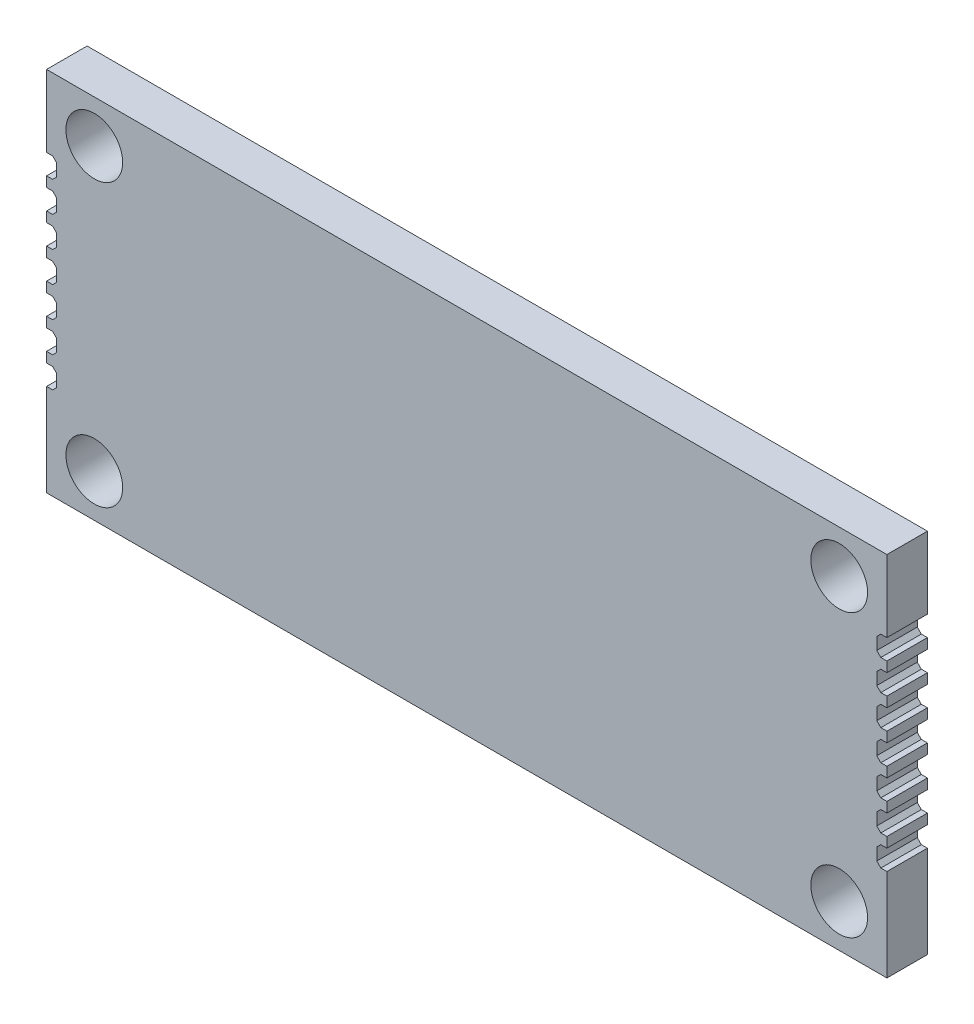
SolidWorks part; units mm, degrees
ref_plane "前视基准面" through (0, 0, 0) normal (0, 0, 1) x (1, 0, 0)
ref_plane "上视基准面" through (0, 0, 0) normal (0, 1, 0) x (1, 0, 0)
ref_plane "右视基准面" through (0, 0, 0) normal (1, 0, 0) x (0, 0, -1)
sketch "草图1" plane through (0, 0, 0) normal (0, 0, 1) x (1, 0, 0)
  line L0 (-20.7373, 13.6) -> (20.7373, 13.6)
  line L1 (20.7373, 13.6) -> (20.7373, -4.5)
  line L2 (20.7373, -4.5) -> (-20.7373, -4.5)
  line L3 (-20.7373, -4.5) -> (-20.7373, 13.6)
extrude "凸台-拉伸1" add sketch "草图1" along normal blind 2
sketch "草图2" plane through (0, 0, 2) normal (0, 0, 1) x (1, 0, 0)
  circle A0 centre (-18.3831, -2.4) radius 1.4
  circle A1 centre (18.3831, -2.4) radius 1.4
  circle A2 centre (18.3831, 11.5) radius 1.4
  circle A3 centre (-18.3831, 11.5) radius 1.4
extrude "切除-拉伸1" cut sketch "草图2" against normal up to next
sketch "草图3" plane through (0, 0, 0) normal (0, 0, -1) x (-1, 0, 0)
  line L0 (-20.7373, 1.05) -> (-20.4373, 1.05) construction
  line L1 (-20.2373, 0.85) -> (-20.4373, 1.05) construction
  line L2 (-20.2373, 0.85) -> (-20.2373, 0.25) construction
  line L3 (-20.4373, 0.05) -> (-20.2373, 0.25) construction
  line L4 (-20.7373, 0.05) -> (-20.4373, 0.05) construction
  line L5 (-20.7373, 1.05) -> (-20.4373, 1.05)
  line L6 (-20.2373, 0.85) -> (-20.4373, 1.05)
  line L7 (-20.2373, 0.85) -> (-20.2373, 0.25)
  line L8 (-20.4373, 0.05) -> (-20.2373, 0.25)
  line L9 (-20.7373, 0.05) -> (-20.4373, 0.05)
  line L10 (-20.7373, 2.55) -> (-20.4373, 2.55)
  line L11 (-20.2373, 2.35) -> (-20.4373, 2.55)
  line L12 (-20.2373, 2.35) -> (-20.2373, 1.75)
  line L13 (-20.4373, 1.55) -> (-20.2373, 1.75)
  line L14 (-20.7373, 1.55) -> (-20.4373, 1.55)
  line L15 (-20.7373, 4.05) -> (-20.4373, 4.05)
  line L16 (-20.2373, 3.85) -> (-20.4373, 4.05)
  line L17 (-20.2373, 3.85) -> (-20.2373, 3.25)
  line L18 (-20.4373, 3.05) -> (-20.2373, 3.25)
  line L19 (-20.7373, 3.05) -> (-20.4373, 3.05)
  line L20 (-20.7373, 5.55) -> (-20.4373, 5.55)
  line L21 (-20.2373, 5.35) -> (-20.4373, 5.55)
  line L22 (-20.2373, 5.35) -> (-20.2373, 4.75)
  line L23 (-20.4373, 4.55) -> (-20.2373, 4.75)
  line L24 (-20.7373, 4.55) -> (-20.4373, 4.55)
  line L25 (-20.7373, 7.05) -> (-20.4373, 7.05)
  line L26 (-20.2373, 6.85) -> (-20.4373, 7.05)
  line L27 (-20.2373, 6.85) -> (-20.2373, 6.25)
  line L28 (-20.4373, 6.05) -> (-20.2373, 6.25)
  line L29 (-20.7373, 6.05) -> (-20.4373, 6.05)
  line L30 (-20.7373, 8.55) -> (-20.4373, 8.55)
  line L31 (-20.2373, 8.35) -> (-20.4373, 8.55)
  line L32 (-20.2373, 8.35) -> (-20.2373, 7.75)
  line L33 (-20.4373, 7.55) -> (-20.2373, 7.75)
  line L34 (-20.7373, 7.55) -> (-20.4373, 7.55)
  line L35 (-20.7373, 10.05) -> (-20.4373, 10.05)
  line L36 (-20.2373, 9.85) -> (-20.4373, 10.05)
  line L37 (-20.2373, 9.85) -> (-20.2373, 9.25)
  line L38 (-20.4373, 9.05) -> (-20.2373, 9.25)
  line L39 (-20.7373, 9.05) -> (-20.4373, 9.05)
  line L40 (-20.7373, -4.5) -> (-20.7373, 13.6) construction
  line L41 (-20.7373, 0.05) -> (-20.7373, 1.05)
  line L42 (-20.7373, 9.05) -> (-20.7373, 10.05)
  line L43 (-20.7373, 7.55) -> (-20.7373, 8.55)
  line L44 (-20.7373, 6.05) -> (-20.7373, 7.05)
  line L45 (-20.7373, 4.55) -> (-20.7373, 5.55)
  line L46 (-20.7373, 1.55) -> (-20.7373, 2.55)
  line L47 (-20.7373, 3.05) -> (-20.7373, 4.05)
  line L50 (20.7373, 3.05) -> (20.7373, 4.05)
  line L51 (20.7373, 1.55) -> (20.7373, 2.55)
  line L52 (20.7373, 4.55) -> (20.7373, 5.55)
  line L53 (20.7373, 6.05) -> (20.7373, 7.05)
  line L54 (20.7373, 7.55) -> (20.7373, 8.55)
  line L55 (20.7373, 9.05) -> (20.7373, 10.05)
  line L56 (20.7373, 0.05) -> (20.7373, 1.05)
  line L57 (20.7373, 9.05) -> (20.4373, 9.05)
  line L58 (20.4373, 9.05) -> (20.2373, 9.25)
  line L59 (20.2373, 9.85) -> (20.2373, 9.25)
  line L60 (20.2373, 9.85) -> (20.4373, 10.05)
  line L61 (20.7373, 10.05) -> (20.4373, 10.05)
  line L62 (20.7373, 7.55) -> (20.4373, 7.55)
  line L63 (20.4373, 7.55) -> (20.2373, 7.75)
  line L64 (20.2373, 8.35) -> (20.2373, 7.75)
  line L65 (20.2373, 8.35) -> (20.4373, 8.55)
  line L66 (20.7373, 8.55) -> (20.4373, 8.55)
  line L67 (20.7373, 6.05) -> (20.4373, 6.05)
  line L68 (20.4373, 6.05) -> (20.2373, 6.25)
  line L69 (20.2373, 6.85) -> (20.2373, 6.25)
  line L70 (20.2373, 6.85) -> (20.4373, 7.05)
  line L71 (20.7373, 7.05) -> (20.4373, 7.05)
  line L72 (20.7373, 4.55) -> (20.4373, 4.55)
  line L73 (20.4373, 4.55) -> (20.2373, 4.75)
  line L74 (20.2373, 5.35) -> (20.2373, 4.75)
  line L75 (20.2373, 5.35) -> (20.4373, 5.55)
  line L76 (20.7373, 5.55) -> (20.4373, 5.55)
  line L77 (20.7373, 3.05) -> (20.4373, 3.05)
  line L78 (20.4373, 3.05) -> (20.2373, 3.25)
  line L79 (20.2373, 3.85) -> (20.2373, 3.25)
  line L80 (20.2373, 3.85) -> (20.4373, 4.05)
  line L81 (20.7373, 4.05) -> (20.4373, 4.05)
  line L82 (20.7373, 1.55) -> (20.4373, 1.55)
  line L83 (20.4373, 1.55) -> (20.2373, 1.75)
  line L84 (20.2373, 2.35) -> (20.2373, 1.75)
  line L85 (20.2373, 2.35) -> (20.4373, 2.55)
  line L86 (20.7373, 2.55) -> (20.4373, 2.55)
  line L87 (20.7373, 0.05) -> (20.4373, 0.05)
  line L88 (20.4373, 0.05) -> (20.2373, 0.25)
  line L89 (20.2373, 0.85) -> (20.2373, 0.25)
  line L90 (20.2373, 0.85) -> (20.4373, 1.05)
  line L91 (20.7373, 1.05) -> (20.4373, 1.05)
extrude "切除-拉伸2" cut sketch "草图3" against normal up to next
